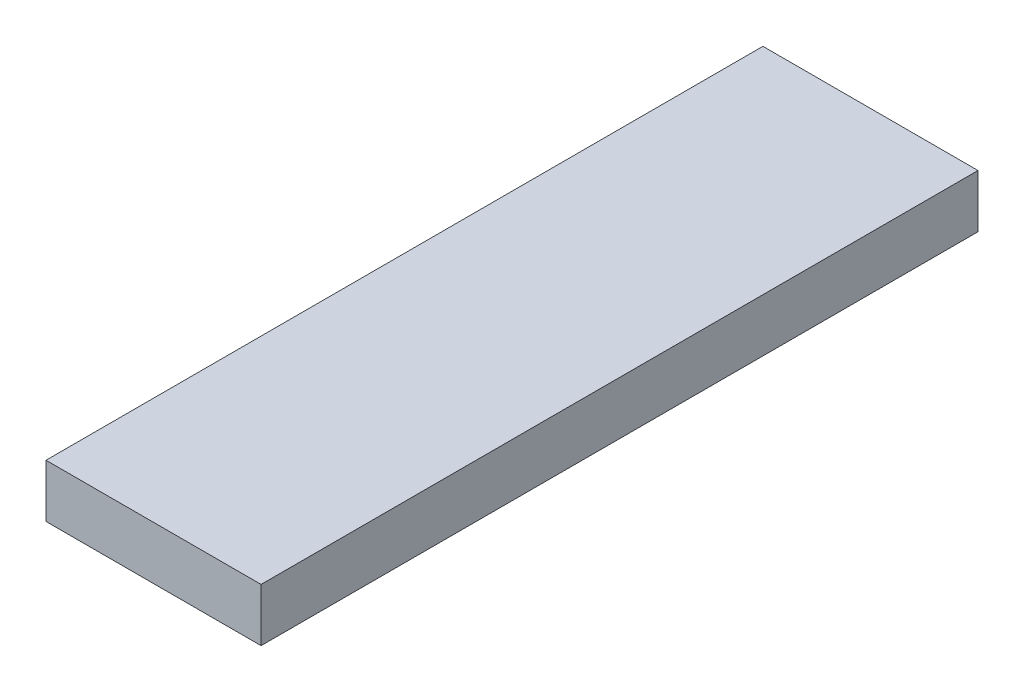
SolidWorks part; units mm, degrees
ref_plane "Front Plane" through (0, 0, 0) normal (0, 0, 1) x (1, 0, 0)
ref_plane "Top Plane" through (0, 0, 0) normal (0, 1, 0) x (1, 0, 0)
ref_plane "Right Plane" through (0, 0, 0) normal (1, 0, 0) x (0, 0, -1)
sketch "Sketch1" plane through (0, 0, 0) normal (0, 1, 0) x (1, 0, 0)
  line L0 (0, 0) -> (19.05, 0)
  line L1 (19.05, 0) -> (19.05, 63.5)
  line L2 (19.05, 63.5) -> (0, 63.5)
  line L4 (0, 63.5) -> (0, 0)
  line L5 (0, 0) -> (12.7, 12.7) construction
  point P3 (6.35, 6.35)
  point P7 (13.5696, 13.5696)
  dimension "D1" = 19.05
  dimension "D2" = 63.5
  dimension "D5" = 45
  dimension "D6" = 6.35
  dimension "D7" = 10.21
extrude "Extrude1" add sketch "Sketch1" along normal blind 4.699
